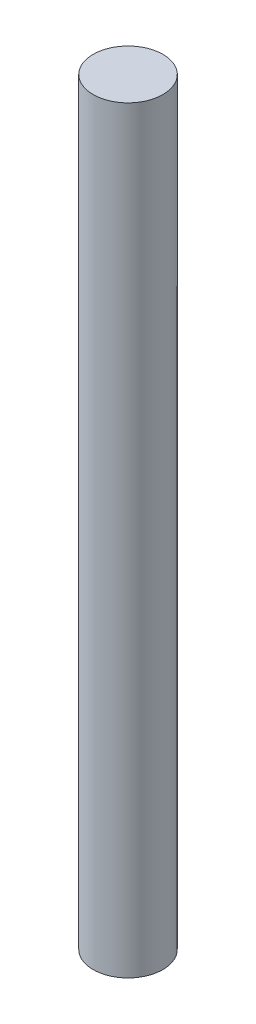
SolidWorks part; units mm, degrees
ref_plane "Front Plane" through (0, 0, 0) normal (0, 0, 1) x (1, 0, 0)
ref_plane "Top Plane" through (0, 0, 0) normal (0, 1, 0) x (1, 0, 0)
ref_plane "Right Plane" through (0, 0, 0) normal (1, 0, 0) x (0, 0, -1)
sketch "Sketch1" plane through (0, 0, 0) normal (0, 1, 0) x (1, 0, 0)
  circle A0 centre (0, 0) radius 1.7526
  dimension "D1" = 3.5052
extrude "Boss-Extrude1" add sketch "Sketch1" along normal blind 38.1
